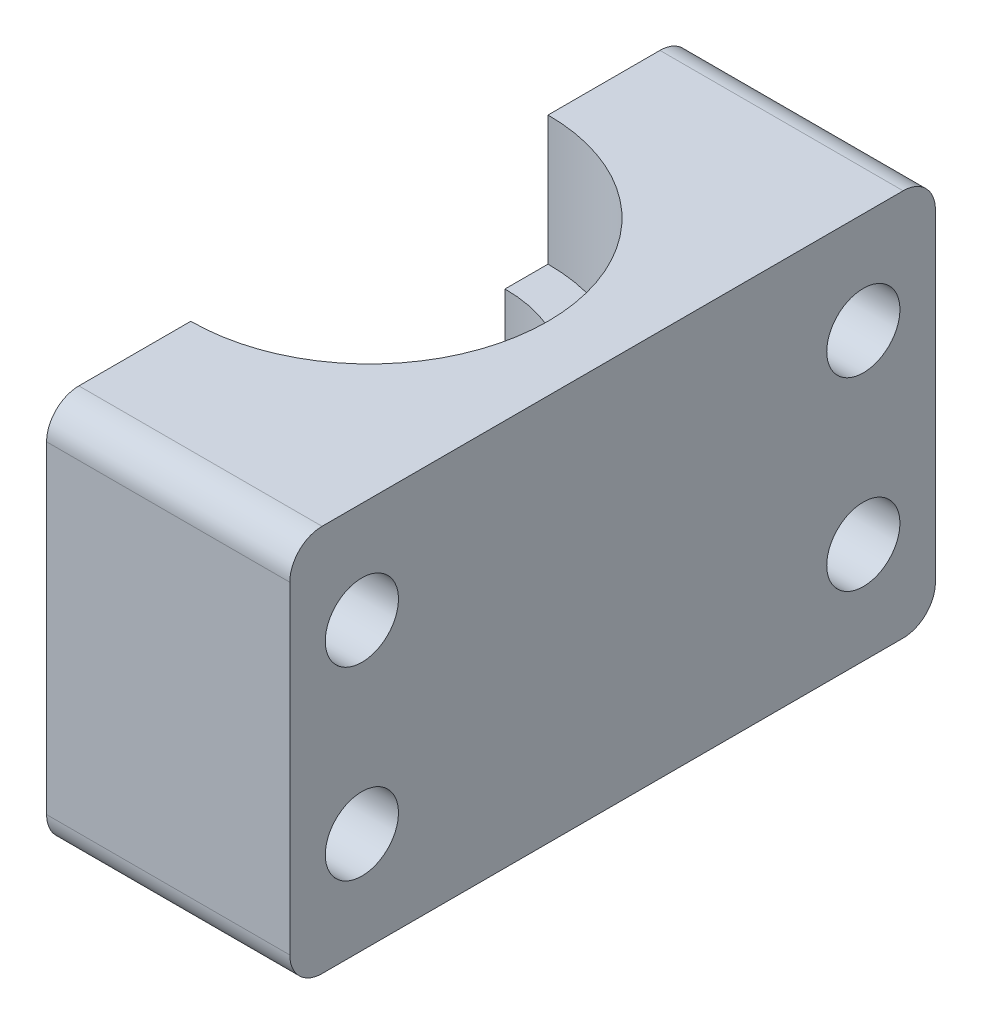
SolidWorks part; units mm, degrees
ref_plane "Front Plane" through (0, 0, 0) normal (0, 0, 1) x (1, 0, 0)
ref_plane "Top Plane" through (0, 0, 0) normal (0, 1, 0) x (1, 0, 0)
ref_plane "Right Plane" through (0, 0, 0) normal (1, 0, 0) x (0, 0, -1)
sketch "Sketch8" plane through (0, 0, 0) normal (1, 0, 0) x (0, 0, -1)
  line L1 (-15, 50) -> (15, 50)
  line L2 (-15, 50) -> (-15, -50)
  line L3 (-15, -50) -> (15, -50)
  line L4 (15, 50) -> (15, -50)
  line L5 (-15, 50) -> (15, -50) construction
  line L6 (-15, -50) -> (15, 50) construction
  point P0 (0, 0)
  dimension "D1" = 30
  dimension "D2" = 100
extrude "Boss-Extrude1" add sketch "Sketch8" along normal blind 100
sketch "Sketch7" plane through (0, 0, 0) normal (1, 0, 0) x (0, 0, -1)
  line L0 (-8.3, 9) -> (-150, 9)
  line L1 (15, 50) -> (-15, 50) construction
  line L2 (-8.3, 9) -> (-8.3, 3)
  line L3 (-8.3, 3) -> (-6.3, 3)
  line L4 (-6.3, 3) -> (-6.3, -3)
  line L5 (-6.3, -3) -> (-8.3, -3)
  line L6 (-8.3, -3) -> (-8.3, -9)
  line L11 (-8.3, -9) -> (-150, -9)
  line L12 (-150, -9) -> (-150, -50)
  line L13 (0, -50) -> (0, 50)
  line L14 (0, 55) -> (0, -55) construction
  line L15 (-150, 9) -> (-150, 50)
  line L16 (-150, 50) -> (0, 50)
  line L17 (-150, -50) -> (0, -50)
  line L18 (-15, -50) -> (15, -50) construction
  line L19 (-15, 9) -> (-15, -9) construction
  line L20 (-15, 50) -> (-15, -50) construction
  line L22 (16.5, 0) -> (-16.5, 0) construction
  point P29 (-15, 0)
  dimension "D1" = 8.3
  dimension "D2" = 6
  dimension "D3" = 6.3
  dimension "D4" = 6
  dimension "D5" = 18
  dimension "D9" = 150
revolve "Cut-Revolve3" cut sketch "Sketch7" angle 360 about L13
sketch "Sketch9" plane through (0, 9, 0) normal (0, 1, 0) x (1, 0, 0)
  line L0 (-55, 0) -> (55, 0) construction
  line L1 (11.3, -15) -> (100, -15)
  line L2 (11.3, -15) -> (11.3, 15)
  line L3 (11.3, 15) -> (100, 15)
  line L4 (100, -15) -> (100, 15)
  line L5 (11.3, -15) -> (100, 15) construction
  line L6 (11.3, 15) -> (100, -15) construction
  line L7 (100, 15) -> (100, -15) construction
  line L8 (0, -15) -> (100, -15) construction
  line L9 (8.3, 15) -> (8.3, -15) construction
  line L10 (100, 15) -> (0, 15) construction
  arc A1 (0, -8.3) -> (0, 8.3) centre (0, 0) ccw construction
  point P0 (55.65, 0)
  dimension "D1" = 3
extrude "Cut-Extrude1" cut sketch "Sketch9" against normal through all
sketch "Sketch10" plane through (0, 0, 0) normal (-1, 0, 0) x (0, 0, 1)
  line L0 (-11.65, 4.3) -> (-11.65, 9) construction
  line L1 (-11.65, -4.3) -> (11.65, -4.3) construction
  line L2 (-11.65, -4.3) -> (-11.65, 4.3) construction
  line L3 (-11.65, 4.3) -> (11.65, 4.3) construction
  line L4 (11.65, -4.3) -> (11.65, 4.3) construction
  line L5 (-11.65, -4.3) -> (11.65, 4.3) construction
  line L6 (-11.65, 4.3) -> (11.65, -4.3) construction
  line L7 (-15, 9) -> (-8.3, 9) construction
  circle A0 centre (-11.65, 4.3) radius 1.7
  circle A1 centre (-11.65, -4.3) radius 1.7
  circle A2 centre (11.65, -4.3) radius 1.7
  circle A3 centre (11.65, 4.3) radius 1.7
  point P0 (0, 0)
  dimension "D1" = 3.4
  dimension "D2" = 4.7
extrude "Cut-Extrude2" cut sketch "Sketch10" against normal through all
fillet "Fillet1" radius 1.5 4 edges at (5.65, 9, -15) (5.65, -9, -15) (5.65, -9, 15) (5.65, 9, 15)
equation "\"linear_bearing_l\"= 35"
equation "\"linear_bearing_d\"= 12"
equation "\"t\"= 3"
equation "\"axes_offset\"= 44.5"
equation "\"fan_b\"= 30"
equation "\"E3D_r\"= 12.8"
equation "\"fan_screws_b\"= 24"
equation "\"fan_screws_l\"= 15"
equation "\"M3_tap_d\"= 2.6"
equation "\"M3_d\"= 3.4"
equation "\"E3D_screws_l\"= 15"
equation "\"M3_nut_s\"= 5.9"
equation "\"M3_nut_m\"= 1.8"
equation "\"cable_ties_d\"= 3"
equation "\"D1@Sketch8\"=\"fan_b\""
equation "\"D2@Sketch8\"=100"
equation "\"D1@Sketch9\"=\"t\""
equation "\"D1@Sketch10\"=\"M3_d\""
equation "\"D2@Sketch10\"=\"M3_d\" / 2 + \"t\""
equation "\"D1@Fillet1\"=\"t\" / 2"
